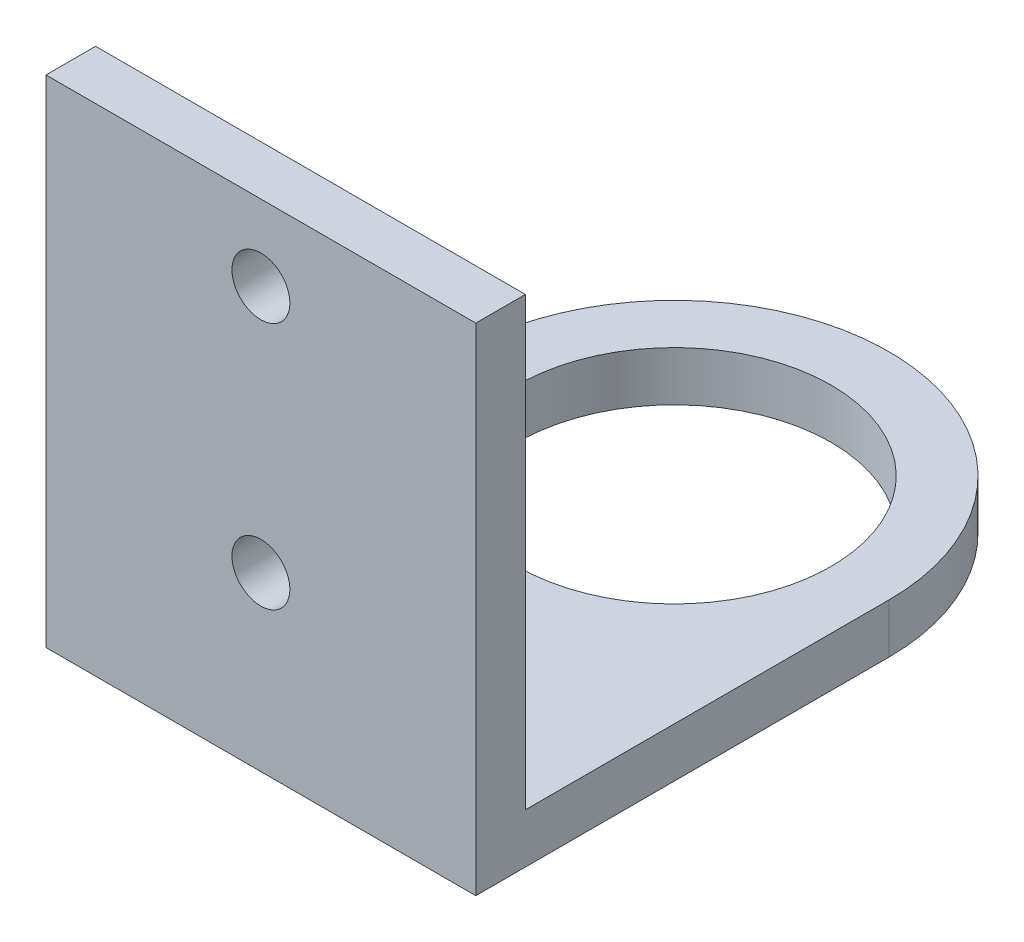
SolidWorks part; units mm, degrees
ref_plane "前视基准面" through (0, 0, 0) normal (0, 0, 1) x (1, 0, 0)
ref_plane "上视基准面" through (0, 0, 0) normal (0, 1, 0) x (1, 0, 0)
ref_plane "右视基准面" through (0, 0, 0) normal (1, 0, 0) x (0, 0, -1)
sketch "草图1" plane through (0, 0, 0) normal (0, 1, 0) x (1, 0, 0)
  line L0 (-13, 0) -> (-13, -25)
  line L1 (-13, -25) -> (13, -25)
  line L2 (13, -25) -> (13, 0)
  circle A0 centre (0, 0) radius 9.5
  circle A1 centre (0, 0) radius 13
  dimension "D1" = 25
  dimension "D2" = 26
  dimension "D3" = 19
extrude "凸台-拉伸1" add sketch "草图1" along normal blind 3 contours A1 A0 | A1 L0 L1 L2
sketch "草图2" plane through (0, 0, 25) normal (0, 0, 1) x (1, 0, 0)
  line L0 (-13, 0) -> (-13, 30)
  line L1 (-13, 30) -> (13, 30)
  line L2 (13, 30) -> (13, 0)
  line L3 (13, 0) -> (-13, 0)
  dimension "D1" = 30
extrude "凸台-拉伸2" add sketch "草图2" against normal blind 3
sketch "草图3" plane through (0, 0, 22) normal (0, 0, -1) x (-1, 0, 0)
  circle A0 centre (0, 10.4221) radius 1.75
  circle A1 centre (0, 25.4221) radius 1.75
  dimension "D1" = 15
extrude "切除-拉伸1" cut sketch "草图3" against normal blind 3
